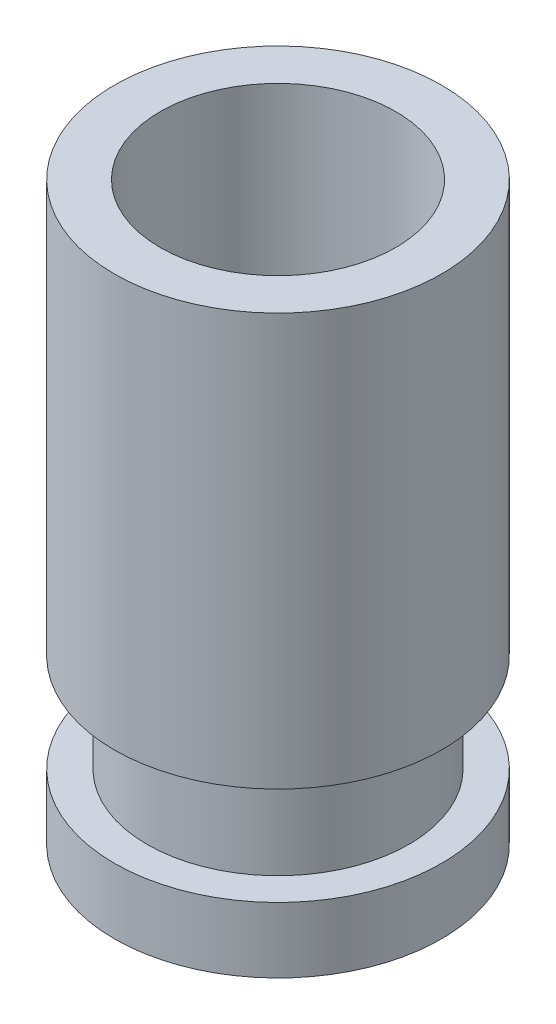
SolidWorks part; units mm, degrees
ref_plane "Front Plane" through (0, 0, 0) normal (0, 0, 1) x (1, 0, 0)
ref_plane "Top Plane" through (0, 0, 0) normal (0, 1, 0) x (1, 0, 0)
ref_plane "Right Plane" through (0, 0, 0) normal (1, 0, 0) x (0, 0, -1)
sketch "Sketch1" plane through (0, 0, 0) normal (0, 1, 0) x (1, 0, 0)
  circle A0 centre (0, 0) radius 25
  circle A1 centre (0, 0) radius 18
  dimension "D1" = 50
  dimension "D2" = 36
extrude "Boss-Extrude1" add sketch "Sketch1" along normal blind 10
sketch "Sketch2" plane through (0, 10, 0) normal (0, 1, 0) x (1, 0, 0)
  circle A0 centre (0, 0) radius 18
  circle A1 centre (0, 0) radius 20
  dimension "D1" = 40
extrude "Boss-Extrude2" add sketch "Sketch2" along normal blind 15
sketch "Sketch3" plane through (0, 25, 0) normal (0, 1, 0) x (1, 0, 0)
  circle A0 centre (0, 0) radius 18
  circle A1 centre (0, 0) radius 25
  dimension "D1" = 50
extrude "Boss-Extrude3" add sketch "Sketch3" along normal blind 63
